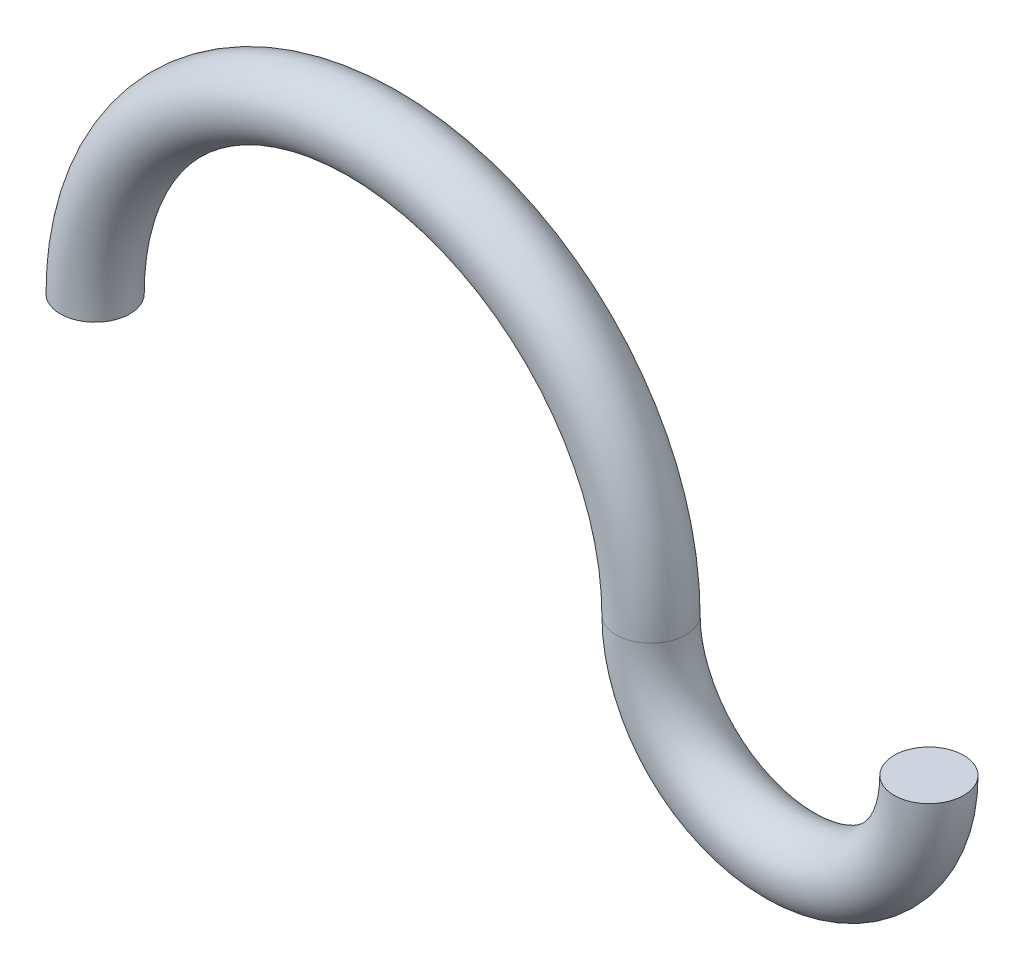
SolidWorks part; units mm, degrees
ref_plane "前视基准面" through (0, 0, 0) normal (0, 0, 1) x (1, 0, 0)
ref_plane "上视基准面" through (0, 0, 0) normal (0, 1, 0) x (1, 0, 0)
ref_plane "右视基准面" through (0, 0, 0) normal (1, 0, 0) x (0, 0, -1)
other "Configuration Table"
sketch "草图1" plane through (0, 0, 0) normal (0, 0, 1) x (1, 0, 0)
  line L0 (-50, 0) -> (10, 0) construction
  arc A0 (10, 0) -> (-10, 0) centre (0, 0) cw
  arc A1 (-10, 0) -> (-50, 0) centre (-30, 0) ccw
  dimension "D1" = 10
  dimension "D2" = 20
sketch "草图2" plane through (0, 0, 0) normal (0, 1, 0) x (1, 0, 0)
  line L0 (-50, 0) -> (10, 0) construction
  circle A0 centre (-50, 0) radius 2.5
  dimension "D1" = 5
sweep "扫描1" add profiles "草图2" path "草图1"
